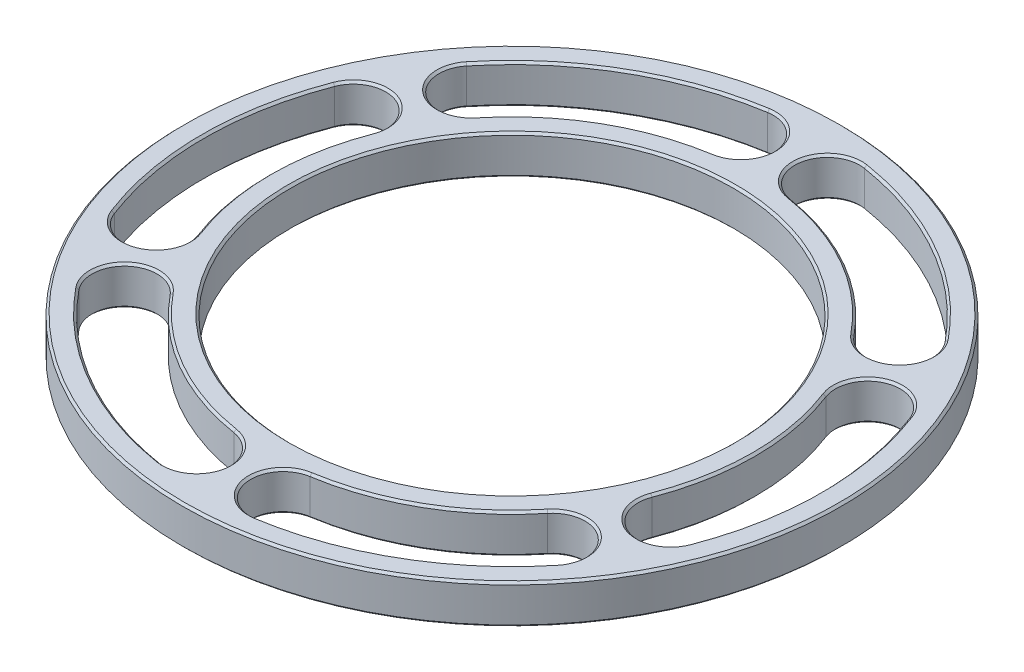
SolidWorks part; units mm, degrees
material "Delrin 2700 NC010, Low Viscosity Acetal Copolymer (SS)"
ref_plane "Front Plane" through (0, 0, 0) normal (0, 0, 1) x (1, 0, 0)
ref_plane "Top Plane" through (0, 0, 0) normal (0, 1, 0) x (1, 0, 0)
ref_plane "Right Plane" through (0, 0, 0) normal (1, 0, 0) x (0, 0, -1)
sketch "Sketch1" plane through (0, 0, 0) normal (0, 0, 1) x (1, 0, 0)
  line L0 (0, 0) -> (51.1251, 0) construction
  line L1 (51.1251, 0) -> (51.1251, 9)
  line L2 (51.1251, 9) -> (76.1, 9)
  line L3 (76.1, 9) -> (76.1, 0)
  line L4 (76.1, 0) -> (51.1251, 0)
  dimension "D1" = 9
  dimension "D2" = 51.1251
  dimension "D3" = 76.1
ref_axis "Axis1" through (0, 0, 0) along (0, 1, 0)
revolve "Revolve1" add sketch "Sketch1" angle 360 about axis through (0, 0, 0) along (0, 1, 0)
sketch "Sketch2" plane through (0, 9, 0) normal (0, 1, 0) x (1, 0, 0)
  line L0 (0, 76.1) -> (0, -76.1) construction
  line L1 (65.9045, 38.05) -> (-65.9045, -38.05) construction
  line L2 (-65.9045, 38.05) -> (65.9045, -38.05) construction
  line L3 (0, 0) -> (-63.6125, 0) construction
  line L4 (-53.1568, 33.5769) -> (-42.3753, 27.3521) construction
  line L5 (-55.6568, 29.2467) -> (-55.9334, 29.4064) construction
  circle A0 centre (0, 0) radius 76.1 construction
  arc A1 (-59.4006, 22.7624) -> (-59.4006, -22.7624) centre (0, 0) ccw construction
  arc A2 (-66.3923, 25.4416) -> (-66.3923, -25.4416) centre (0, 0) ccw
  arc A3 (-52.4089, 20.0832) -> (-52.4089, -20.0832) centre (0, 0) ccw
  arc A4 (-52.4089, 20.0832) -> (-66.3923, 25.4416) centre (-59.4006, 22.7624) ccw
  arc A5 (-66.3923, -25.4416) -> (-52.4089, -20.0832) centre (-59.4006, -22.7624) ccw
  circle A6 centre (0, 0) radius 51.1251 construction
  arc A7 (-9.9875, 62.8236) -> (-49.4131, 40.0612) centre (0, 0) ccw construction
  arc A8 (-11.163, 70.2182) -> (-55.2292, 44.7766) centre (0, 0) ccw
  arc A9 (-8.8119, 55.429) -> (-43.597, 35.3458) centre (0, 0) ccw
  arc A10 (-8.8119, 55.429) -> (-11.163, 70.2182) centre (-9.9875, 62.8236) ccw
  arc A11 (-55.2292, 44.7766) -> (-43.597, 35.3458) centre (-49.4131, 40.0612) ccw
  arc A12 (49.4131, 40.0612) -> (9.9875, 62.8236) centre (0, 0) ccw construction
  arc A13 (55.2292, 44.7766) -> (11.163, 70.2182) centre (0, 0) ccw
  arc A14 (43.597, 35.3458) -> (8.8119, 55.429) centre (0, 0) ccw
  arc A15 (43.597, 35.3458) -> (55.2292, 44.7766) centre (49.4131, 40.0612) ccw
  arc A16 (11.163, 70.2182) -> (8.8119, 55.429) centre (9.9875, 62.8236) ccw
  arc A17 (59.4006, -22.7624) -> (59.4006, 22.7624) centre (0, 0) ccw construction
  arc A18 (66.3923, -25.4416) -> (66.3923, 25.4416) centre (0, 0) ccw
  arc A19 (52.4089, -20.0832) -> (52.4089, 20.0832) centre (0, 0) ccw
  arc A20 (52.4089, -20.0832) -> (66.3923, -25.4416) centre (59.4006, -22.7624) ccw
  arc A21 (66.3923, 25.4416) -> (52.4089, 20.0832) centre (59.4006, 22.7624) ccw
  arc A22 (9.9875, -62.8236) -> (49.4131, -40.0612) centre (0, 0) ccw construction
  arc A23 (11.163, -70.2182) -> (55.2292, -44.7766) centre (0, 0) ccw
  arc A24 (8.8119, -55.429) -> (43.597, -35.3458) centre (0, 0) ccw
  arc A25 (8.8119, -55.429) -> (11.163, -70.2182) centre (9.9875, -62.8236) ccw
  arc A26 (55.2292, -44.7766) -> (43.597, -35.3458) centre (49.4131, -40.0612) ccw
  arc A27 (-49.4131, -40.0612) -> (-9.9875, -62.8236) centre (0, 0) ccw construction
  arc A28 (-55.2292, -44.7766) -> (-11.163, -70.2182) centre (0, 0) ccw
  arc A29 (-43.597, -35.3458) -> (-8.8119, -55.429) centre (0, 0) ccw
  arc A30 (-43.597, -35.3458) -> (-55.2292, -44.7766) centre (-49.4131, -40.0612) ccw
  arc A31 (-11.163, -70.2182) -> (-8.8119, -55.429) centre (-9.9875, -62.8236) ccw
  point P13 (-63.6125, 0)
  point P25 (-31.8063, 55.0901)
  point P34 (31.8063, 55.0901)
  point P41 (63.6125, 0)
  point P48 (31.8063, -55.0901)
  point P55 (-31.8063, -55.0901)
  point P60 (-54.1285, 34.2451)
  point P63 (-56.7213, 29.7541)
  dimension "D3" = 5
  dimension "D4" = 5
  dimension "D1" = 60
  dimension "D2" = 60
  dimension "D5" = 30
  dimension "D7" = 5
  dimension "D6" = 6
extrude "Cut-Extrude1" cut sketch "Sketch2" against normal blind 10 contours A2 A5 A3 A4
chamfer "Chamfer3" distance 0.5 angle 45 4 edges at (0, 0, -76.1) (0, 9, -76.1) (0, 0, -51.1251) (0, 9, -51.1251)
chamfer "Chamfer4" distance 0.5 angle 45 8 edges at (-56.7213, 9, -29.7541) (-56.7213, 0, 29.7541) (-71.1, 0, 0) (-56.1251, 0, 0) (-56.7213, 0, -29.7541) (-71.1, 9, 0) (-56.1251, 9, 0) (-56.7213, 9, 29.7541)
pattern_circular "CirPattern1" count 6 over 360 about axis through (0, 0, 0) along (0, 1, 0) of "Cut-Extrude1", "Chamfer4"
